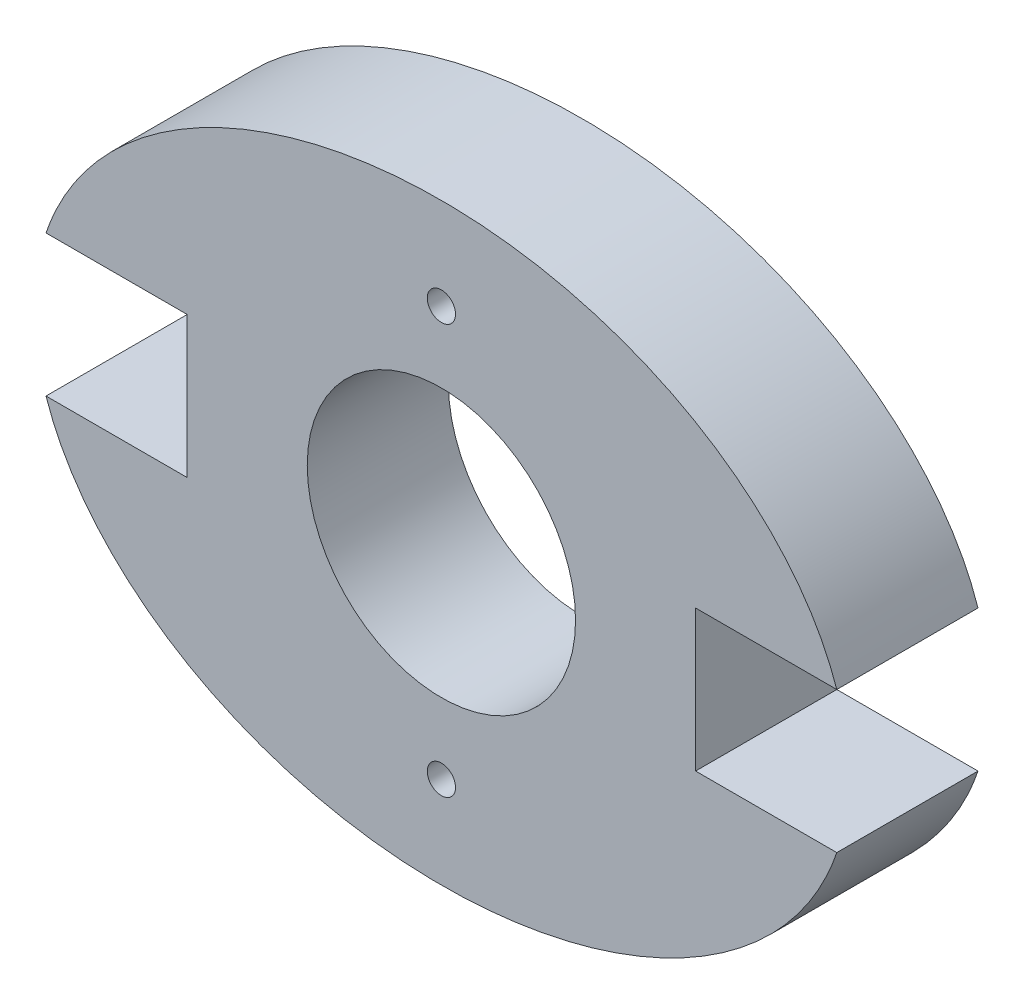
SolidWorks part; units mm, degrees
material "Balsa"
ref_plane "Plan de face" through (0, 0, 0) normal (0, 0, 1) x (1, 0, 0)
ref_plane "Plan de dessus" through (0, 0, 0) normal (0, 1, 0) x (1, 0, 0)
ref_plane "Plan de droite" through (0, 0, 0) normal (1, 0, 0) x (0, 0, -1)
sketch "Esquisse1" plane through (0, 0, 0) normal (0, 0, 1) x (1, 0, 0)
  line L0 (-20.8509, -2.5) -> (20.8509, -2.5) construction
  line L1 (0, 7.2545) -> (0, -7.2545) construction
  line L2 (-14.4145, 0) -> (14.4145, 0) construction
  line L3 (-20.8509, 2.5) -> (20.8509, 2.5) construction
  line L4 (-20.8509, -2.5) -> (20.8509, 2.5) construction
  line L5 (20.8509, -2.5) -> (-20.8509, 2.5) construction
  line L6 (-14, 2.5) -> (-9, 2.5)
  line L7 (14, 2.5) -> (9, 2.5)
  line L8 (14, -2.5) -> (9, -2.5)
  line L9 (-14, -2.5) -> (-9, -2.5)
  line L10 (-9, 2.5) -> (-9, -2.5)
  line L11 (9, 2.5) -> (9, -2.5)
  circle A5 centre (0, 7.2545) radius 0.5
  circle A6 centre (0, -7.2545) radius 0.5
  circle A9 centre (0, 0) radius 4.75
  ellipse E0 centre (0, 0) end of major axis (14.4145, 0) minor radius 10.5 (-14, 2.5) -> (14, 2.5) cw
  ellipse E1 centre (0, 0) end of major axis (14.4145, 0) minor radius 10.5 (-14, -2.5) -> (14, -2.5) ccw
  point P1 (0, 0)
  dimension "D2" = 9.5
  dimension "D3" = 5
  dimension "D7" = 1
  dimension "D8" = 1
  dimension "D1" = 5
  dimension "D4" = 18
  dimension "D5" = 28
  dimension "D6" = 21
extrude "Boss.-Extru.1" add sketch "Esquisse1" along normal blind 5
